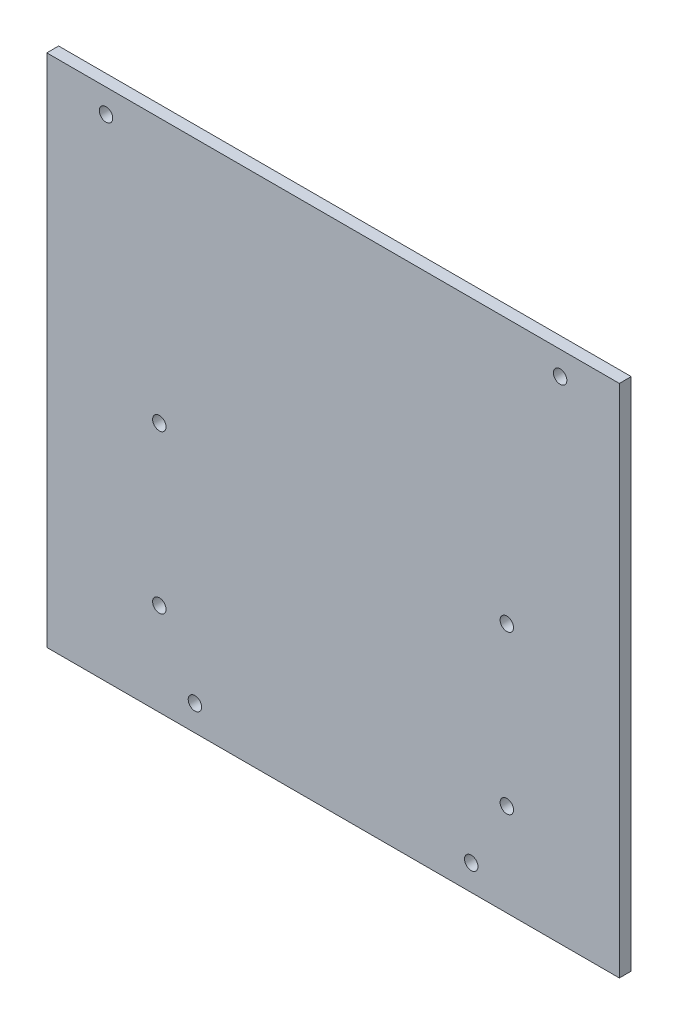
SolidWorks part; units mm, degrees
ref_plane "Front Plane" through (0, 0, 0) normal (0, 0, 1) x (1, 0, 0)
ref_plane "Top Plane" through (0, 0, 0) normal (0, 1, 0) x (1, 0, 0)
ref_plane "Right Plane" through (0, 0, 0) normal (1, 0, 0) x (0, 0, -1)
sketch "Sketch1" plane through (0, 0, 0) normal (0, 0, 1) x (1, 0, 0)
  line L0 (-71.9, 130.4) -> (-75.9, 130.4) construction
  line L1 (-72.5, 0) -> (72.5, 0)
  line L2 (-72.5, 0) -> (-72.5, 130.4)
  line L3 (-72.5, 130.4) -> (72.5, 130.4)
  line L4 (72.5, 0) -> (72.5, 130.4)
  line L5 (0, 0) -> (0, 130.4) construction
  circle A0 centre (-56.5, 6.5) radius 1.7 construction
  circle A1 centre (56.5, 6.5) radius 1.7 construction
  dimension "D2" = 3.4
  dimension "D3" = 16
  dimension "D4" = 6.5
  dimension "D5" = 145
extrude "Boss-Extrude1" add sketch "Sketch1" along normal blind 3
sketch "Sketch3" plane through (0, 0, 3) normal (0, 0, 1) x (1, 0, 0)
  circle A0 centre (-57.5, 124.4) radius 1.7
  circle A1 centre (57.5, 124.4) radius 1.7
  circle A2 centre (-44, 63.4388) radius 1.7
  circle A3 centre (-44, 23.4388) radius 1.7
  circle A4 centre (44, 23.4388) radius 1.7
  circle A5 centre (44, 63.4388) radius 1.7
  circle A6 centre (-34.9875, 6.5) radius 1.7
  circle A7 centre (34.9875, 6.5) radius 1.7
  dimension "D1" = 3.4
  dimension "D2" = 3.4
  dimension "D3" = 3.4
extrude "dependent_holes" cut sketch "Sketch3" against normal blind 10
